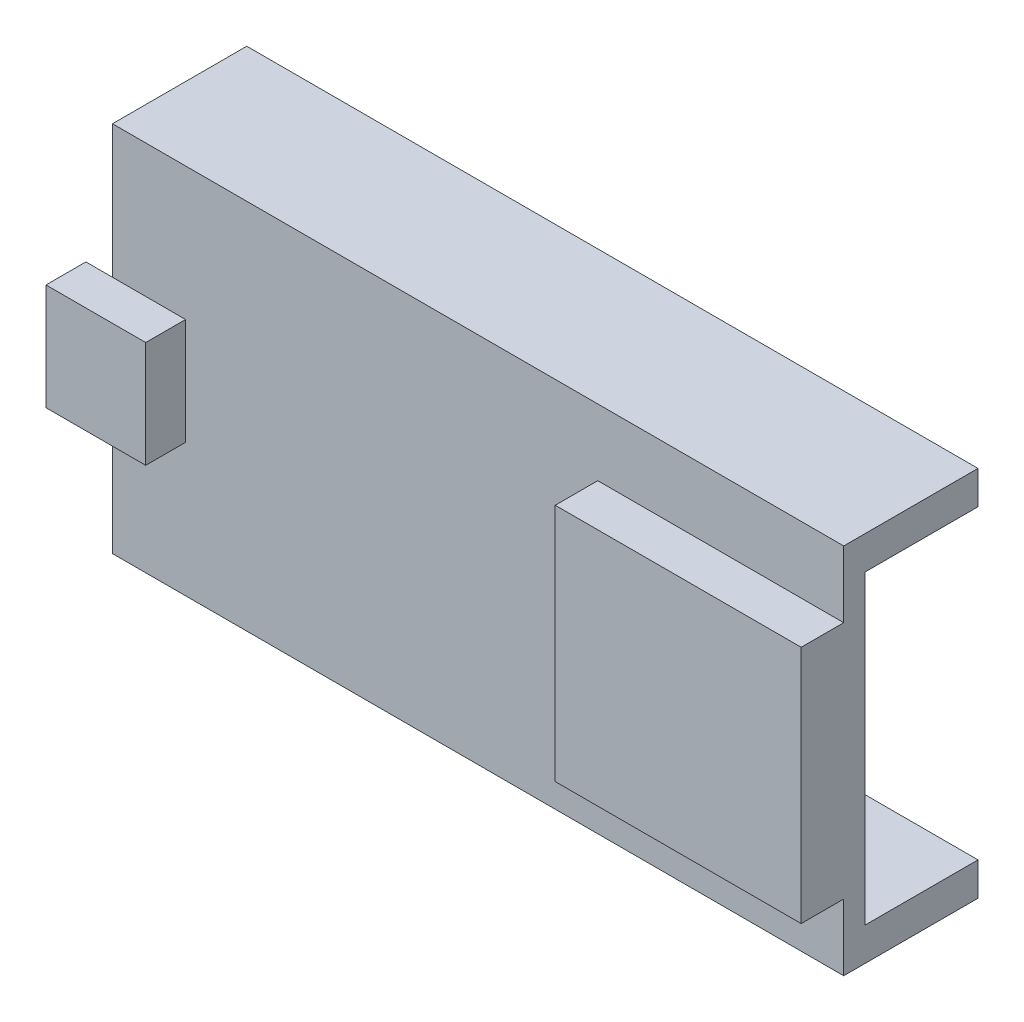
SolidWorks part; units mm, degrees
ref_plane "Front Plane" through (0, 0, 0) normal (0, 0, 1) x (1, 0, 0)
ref_plane "Top Plane" through (0, 0, 0) normal (0, 1, 0) x (1, 0, 0)
ref_plane "Right Plane" through (0, 0, 0) normal (1, 0, 0) x (0, 0, -1)
sketch "Sketch1" plane through (0, 0, 0) normal (0, 0, 1) x (1, 0, 0)
  line L0 (-27.5, -14) -> (27.5, -14)
  line L1 (27.5, -14) -> (27.5, 14)
  line L2 (27.5, 14) -> (-27.5, 14)
  line L3 (-27.5, 14) -> (-27.5, -14)
extrude "PCB" add sketch "Sketch1" along normal blind 1.6
ref_plane "P_Front_m8p5" through (0, 0, -8.5) normal (0, 0, 1) x (1, 0, 0)
sketch "Sketch2" plane through (0, 0, -8.5) normal (0, 0, 1) x (1, 0, 0)
  line L0 (-27.5, -14) -> (27.5, -14)
  line L1 (27.5, -14) -> (27.5, -11.5)
  line L2 (27.5, -11.5) -> (-27.5, -11.5)
  line L3 (-27.5, -11.5) -> (-27.5, -14)
extrude "Header_A" add sketch "Sketch2" along normal blind 8.5
sketch "Sketch3" plane through (0, 0, -8.5) normal (0, 0, 1) x (1, 0, 0)
  line L0 (-27.5, 11.5) -> (27.5, 11.5)
  line L1 (27.5, 11.5) -> (27.5, 14)
  line L2 (27.5, 14) -> (-27.5, 14)
  line L3 (-27.5, 14) -> (-27.5, 11.5)
extrude "Header_B" add sketch "Sketch3" along normal blind 8.5
ref_plane "P_Front_1p6" through (0, 0, 1.6) normal (0, 0, 1) x (1, 0, 0)
sketch "Sketch4" plane through (0, 0, 1.6) normal (0, 0, 1) x (1, 0, 0)
  line L0 (9, -9) -> (27.5, -9)
  line L1 (27.5, -9) -> (27.5, 9)
  line L2 (27.5, 9) -> (9, 9)
  line L3 (9, 9) -> (9, -9)
extrude "WROOM_module" add sketch "Sketch4" along normal blind 3.2
sketch "Sketch5" plane through (0, 0, 1.6) normal (0, 0, 1) x (1, 0, 0)
  line L0 (-29.5, -4) -> (-22, -4)
  line L1 (-22, -4) -> (-22, 4)
  line L2 (-22, 4) -> (-29.5, 4)
  line L3 (-29.5, 4) -> (-29.5, -4)
extrude "USB" add sketch "Sketch5" along normal blind 3
